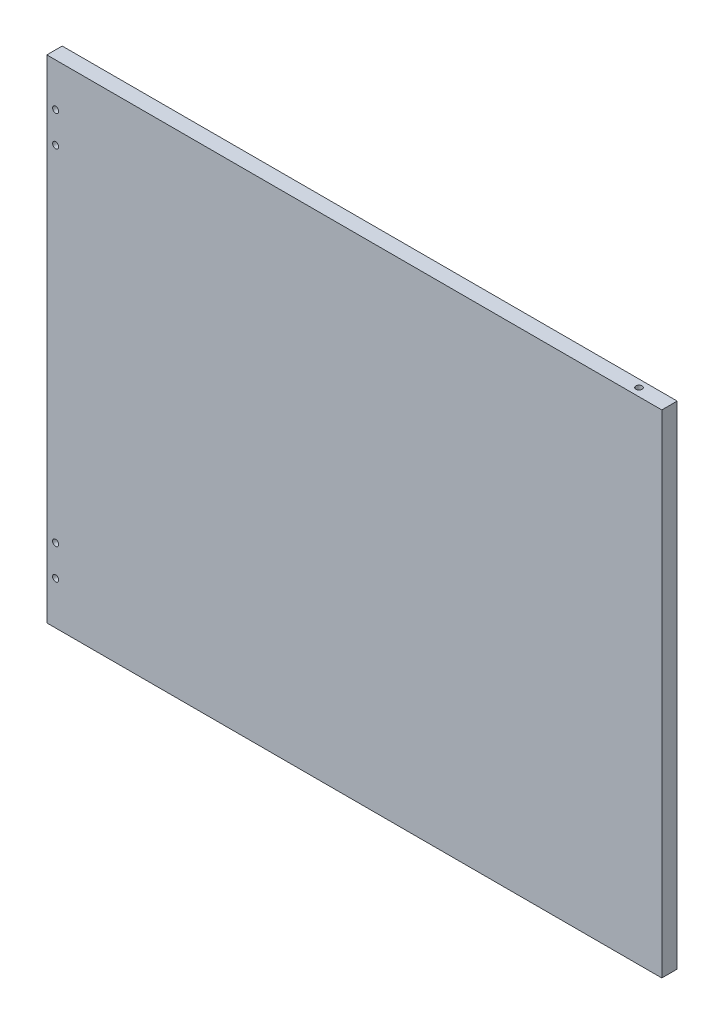
SolidWorks part; units mm, degrees
ref_plane "Płaszczyzna przednia" through (0, 0, 0) normal (0, 0, 1) x (1, 0, 0)
ref_plane "Płaszczyzna górna" through (0, 0, 0) normal (0, 1, 0) x (1, 0, 0)
ref_plane "Płaszczyzna prawa" through (0, 0, 0) normal (1, 0, 0) x (0, 0, -1)
sketch "Szkic1" plane through (0, 0, 0) normal (0, 0, 1) x (1, 0, 0)
  line L1 (0, 0) -> (1000, 0)
  line L2 (0, 0) -> (0, 800)
  line L3 (0, 800) -> (1000, 800)
  line L4 (1000, 0) -> (1000, 800)
  dimension "D1" = 800
  dimension "D2" = 1000
extrude "Dodanie-wyciągnięcie1" add sketch "Szkic1" along normal blind 25
sketch "Szkic2" plane through (0, 0, 0) normal (0, 0, 1) x (1, 0, 0)
  line L3 (0, 400) -> (1000, 400) construction
  line L4 (0, 800) -> (0, 0) construction
  line L5 (1000, 0) -> (1000, 800) construction
  circle A0 centre (14.35, 730) radius 5
  circle A1 centre (14.35, 680) radius 5
  circle A2 centre (14.35, 70) radius 5
  circle A3 centre (14.35, 120) radius 5
  dimension "D1" = 10
  dimension "D2" = 10
  dimension "D7" = 10
  dimension "D8" = 10
  dimension "D3" = 50
  dimension "D4" = 14.35
  dimension "D5" = 14.35
  dimension "D6" = 70
  dimension "D9" = 50
  dimension "D10" = 70
  dimension "D11" = 14.35
  dimension "D12" = 14.35
extrude "Wytnij-wyciągnięcie3" cut sketch "Szkic2" along normal blind 25
sketch "Szkic4" plane through (0, 0, 0) normal (0, 1, 0) x (1, 0, 0)
  circle A0 centre (950, -12) radius 5
  dimension "D1" = 10
  dimension "D2" = 50
  dimension "D3" = 13
extrude "Wytnij-wyciągnięcie4" cut sketch "Szkic4" along normal blind 40
sketch "Szkic5" plane through (0, 0, 0) normal (0, 0, 1) x (1, 0, 0)
  line L0 (0, 400) -> (1000, 400) construction
  line L1 (0, 800) -> (0, 0) construction
  line L2 (1000, 0) -> (1000, 800) construction
ref_plane "Płaszczyzna1" through (0, 400, 0) normal (0, 1, 0) x (1, 0, 0)
mirror "Lustro2" about plane through (0, 400, 0) normal (0, 1, 0) of "Wytnij-wyciągnięcie4"
equation "\"Dodanie-wyciągnięcie1\"= IIF ( \"D2@Szkic1\" < 400 , \"suppressed\" , \"unsuppressed\" )"
